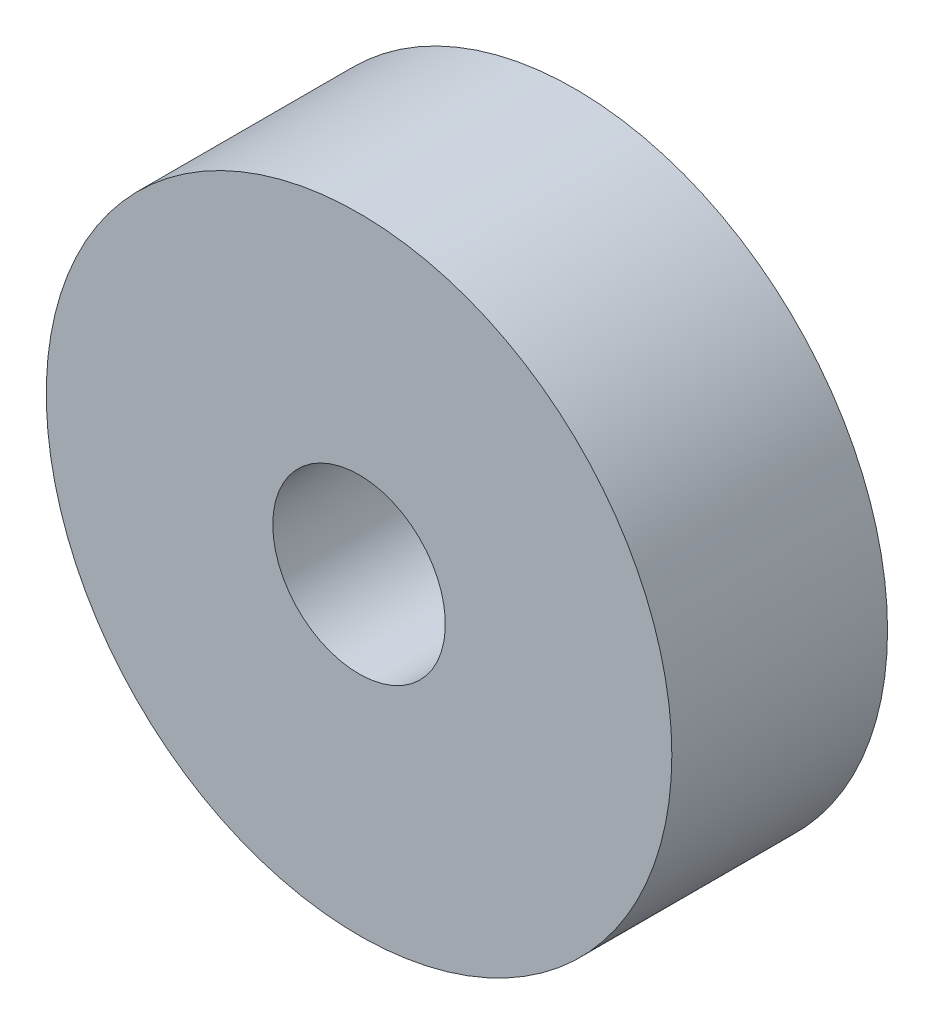
SolidWorks part; units mm, degrees
ref_plane "Front Plane" through (0, 0, 0) normal (0, 0, 1) x (1, 0, 0)
ref_plane "Top Plane" through (0, 0, 0) normal (0, 1, 0) x (1, 0, 0)
ref_plane "Right Plane" through (0, 0, 0) normal (1, 0, 0) x (0, 0, -1)
sketch "Sketch2" plane through (0, 0, 0) normal (0, 0, 1) x (1, 0, 0)
  circle A0 centre (0, 0) radius 18.415
  dimension "D1" = 36.83
extrude "Boss-Extrude1" add sketch "Sketch2" along normal blind 12.7
sketch "Sketch3" plane through (0, 0, 0) normal (0, 0, -1) x (-1, 0, 0)
  circle A0 centre (0, 0) radius 5.08
  dimension "D1" = 10.16
extrude "Cut-Extrude1" cut sketch "Sketch3" against normal through all
